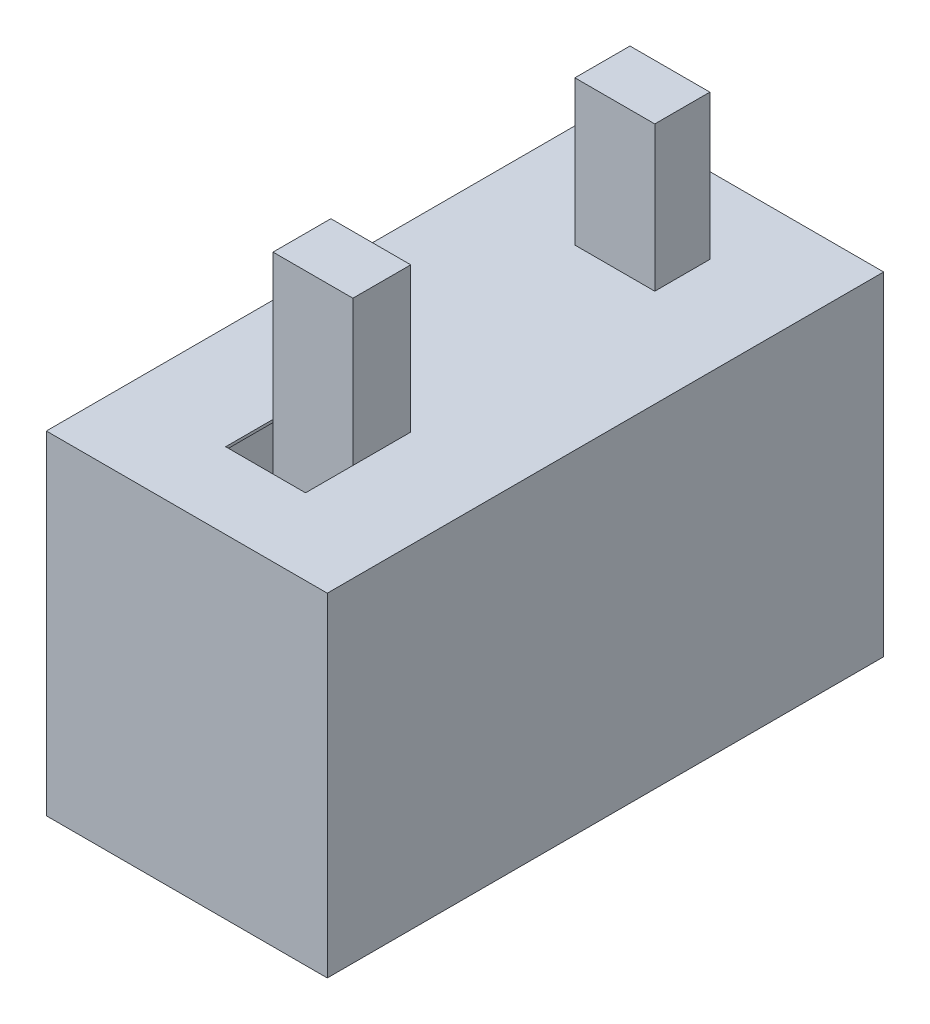
SolidWorks part; units mm, degrees
ref_plane "Plan de face" through (0, 0, 0) normal (0, 0, 1) x (1, 0, 0)
ref_plane "Plan de dessus" through (0, 0, 0) normal (0, 1, 0) x (1, 0, 0)
ref_plane "Plan de droite" through (0, 0, 0) normal (1, 0, 0) x (0, 0, -1)
sketch "Esquisse2" plane through (0, 0, 0) normal (0, 1, 0) x (1, 0, 0)
  line L1 (-55.7367, 99.4742) -> (454.2633, 99.4742)
  line L2 (-55.7367, 99.4742) -> (-55.7367, -910.5258)
  line L3 (-55.7367, -910.5258) -> (454.2633, -910.5258)
  line L4 (454.2633, 99.4742) -> (454.2633, -910.5258)
  dimension "D1" = 510
  dimension "D2" = 1010
extrude "Boss.-Extru.1" add sketch "Esquisse2" along normal blind 5
sketch "Esquisse4" plane through (0, 5, 0) normal (0, 1, 0) x (1, 0, 0)
  line L1 (-55.7367, 99.4742) -> (454.2633, 99.4742)
  line L2 (-55.7367, 99.4742) -> (-55.7367, -910.5258)
  line L3 (-55.7367, -910.5258) -> (454.2633, -910.5258)
  line L4 (454.2633, 99.4742) -> (454.2633, -910.5258)
  line L5 (-50.7367, 94.4742) -> (449.2633, 94.4742)
  line L6 (-50.7367, 94.4742) -> (-50.7367, -905.5258)
  line L7 (-50.7367, -905.5258) -> (449.2633, -905.5258)
  line L8 (449.2633, 94.4742) -> (449.2633, -905.5258)
  dimension "D1" = 500
  dimension "D2" = 1000
  dimension "D3" = 5
  dimension "D4" = 5
extrude "Boss.-Extru.2" add sketch "Esquisse4" along normal blind 595
sketch "Esquisse5" plane through (0, 600, 0) normal (0, 1, 0) x (1, 0, 0)
  line L1 (-55.7367, 99.4742) -> (454.2633, 99.4742)
  line L2 (-55.7367, 99.4742) -> (-55.7367, -910.5258)
  line L3 (-55.7367, -910.5258) -> (454.2633, -910.5258)
  line L4 (454.2633, 99.4742) -> (454.2633, -910.5258)
extrude "Boss.-Extru.3" add sketch "Esquisse5" along normal blind 5
sketch "Esquisse6" plane through (0, 605, 0) normal (0, 1, 0) x (1, 0, 0)
  line L0 (-55.7367, -910.5258) -> (454.2633, -910.5258) construction
  line L1 (131.7633, -581.5258) -> (276.7633, -581.5258)
  line L2 (131.7633, -581.5258) -> (131.7633, -772.5258)
  line L3 (131.7633, -772.5258) -> (276.7633, -772.5258)
  line L4 (276.7633, -581.5258) -> (276.7633, -772.5258)
  line L5 (131.7633, -38.5258) -> (276.7633, -38.5258)
  line L6 (131.7633, -38.5258) -> (131.7633, -138.5258)
  line L7 (131.7633, -138.5258) -> (276.7633, -138.5258)
  line L8 (276.7633, -38.5258) -> (276.7633, -138.5258)
  line L9 (-55.7367, 99.4742) -> (-55.7367, -910.5258) construction
  line L10 (454.2633, 99.4742) -> (-55.7367, 99.4742) construction
  dimension "D1" = 138
  dimension "D2" = 145
  dimension "D3" = 187.5
  dimension "D4" = 191
  dimension "D5" = 100
  dimension "D6" = 145
  dimension "D7" = 187.5
  dimension "D8" = 138
extrude "Enlèv. mat.-Extru.1" cut sketch "Esquisse6" against normal blind 10
sketch "Esquisse8" plane through (0, 5, 0) normal (0, 1, 0) x (1, 0, 0)
  line L0 (276.7633, -772.5258) -> (276.7633, -581.5258) construction
  line L1 (131.7633, -38.5258) -> (276.7633, -38.5258)
  line L2 (131.7633, -38.5258) -> (131.7633, -138.5258)
  line L3 (131.7633, -138.5258) -> (276.7633, -138.5258)
  line L4 (276.7633, -38.5258) -> (276.7633, -138.5258)
  line L5 (131.7633, -581.5258) -> (276.7633, -581.5258)
  line L6 (131.7633, -581.5258) -> (131.7633, -686.5258)
  line L7 (131.7633, -686.5258) -> (276.7633, -686.5258)
  line L8 (276.7633, -581.5258) -> (276.7633, -686.5258)
  line L9 (454.2633, 99.4742) -> (-55.7367, 99.4742) construction
  dimension "D1" = 105
  dimension "D2" = 138
extrude "Boss.-Extru.5" add sketch "Esquisse8" along normal blind 863
